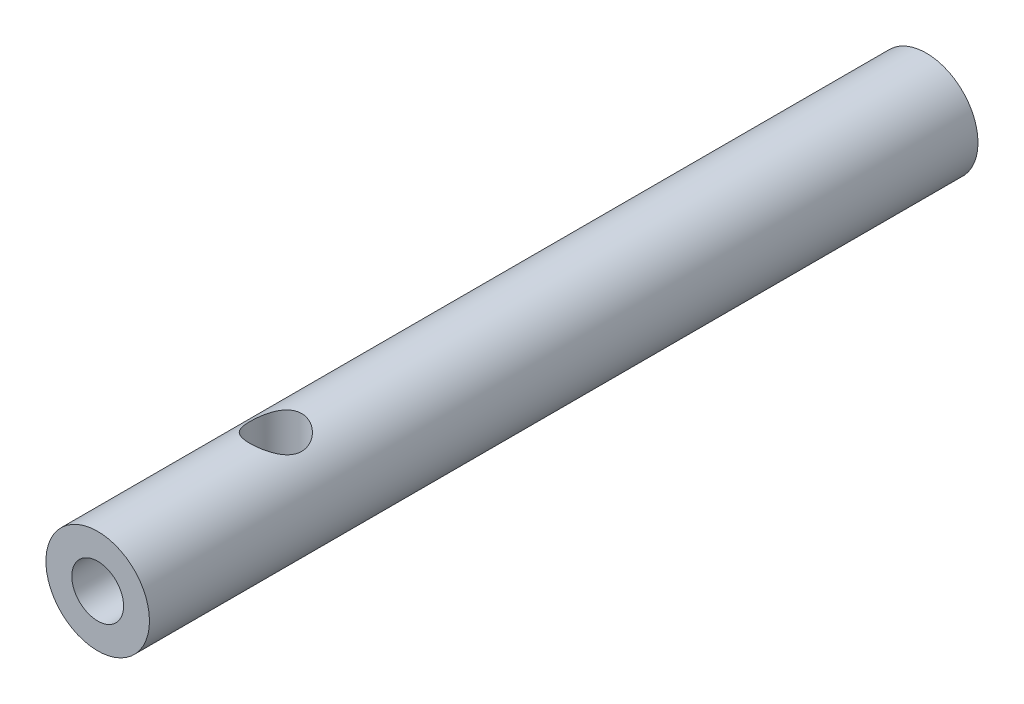
SolidWorks part; units mm, degrees
ref_plane "Front Plane" through (0, 0, 0) normal (0, 0, 1) x (1, 0, 0)
ref_plane "Top Plane" through (0, 0, 0) normal (0, 1, 0) x (1, 0, 0)
ref_plane "Right Plane" through (0, 0, 0) normal (1, 0, 0) x (0, 0, -1)
sketch "Sketch1" plane through (0, 0, 0) normal (0, 0, 1) x (1, 0, 0)
  circle A0 centre (0, 0) radius 6.35
  dimension "D1" = 12.7
extrude "Boss-Extrude1" add sketch "Sketch1" against normal blind 101.6
sketch "Sketch7" plane through (0, 0, -101.6) normal (0, 0, -1) x (-1, 0, 0)
  circle A0 centre (0, 0) radius 3.175
  circle A1 centre (0, 0) radius 6.35 construction
  dimension "D1" = 6.35
extrude "Cut-Extrude4" cut sketch "Sketch7" against normal blind 12.7
sketch "Sketch10" plane through (0, 0, 0) normal (0, 1, 0) x (1, 0, 0)
  circle A0 centre (0, 21.844) radius 3.175
  dimension "D1" = 6.35
  dimension "D2" = 21.844
extrude "Cut-Extrude5" cut sketch "Sketch10" against normal blind 8.636 and the other way blind 7.62 contours A0
sketch "Sketch11" plane through (0, 0, 0) normal (0, 0, 1) x (1, 0, 0)
  circle A0 centre (0, 0) radius 3.175
  dimension "D1" = 6.35
extrude "Cut-Extrude6" cut sketch "Sketch11" against normal blind 12.7
